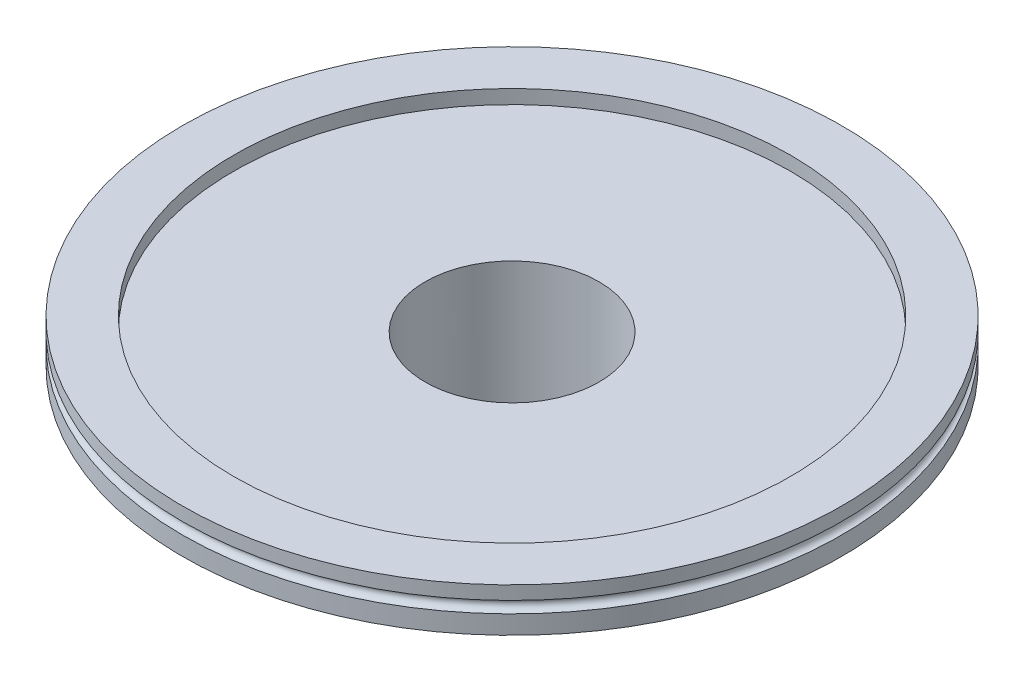
SolidWorks part; units mm, degrees
material "AISI 304"
ref_plane "Front Plane" through (0, 0, 0) normal (0, 0, 1) x (1, 0, 0)
ref_plane "Top Plane" through (0, 0, 0) normal (0, 1, 0) x (1, 0, 0)
ref_plane "Right Plane" through (0, 0, 0) normal (1, 0, 0) x (0, 0, -1)
sketch "Sketch1" plane through (0, 0, 0) normal (0, 0, 1) x (1, 0, 0)
  line L0 (-90, 5.969) -> (-90, -5.969)
  line L1 (-90, -5.969) -> (0, -5.969)
  line L6 (0, -5.969) -> (0, 0) construction
  line L7 (0, 0) -> (-90, 0) construction
  line L12 (-90, 5.969) -> (0, 5.969)
  line L13 (0, 5.969) -> (0, -5.969)
  dimension "D" = 11.938
  dimension "LF_Flange_Diam" = 180
revolve "Blank" add sketch "Sketch1" angle 360 about L13
sketch "Sketch7" plane through (0, 0, 0) normal (0, 0, 1) x (1, 0, 0)
  line L0 (-23.749, -5.969) -> (-23.749, 2.159)
  line L1 (90, 5.969) -> (-90, 5.969) construction
  line L2 (-23.749, 2.159) -> (-76.03, 2.159)
  line L3 (-76.03, 2.159) -> (-76.03, 5.969)
  line L4 (-76.03, 5.969) -> (0, 5.969)
  line L5 (0, 5.969) -> (0, -5.969)
  line L6 (0, -5.969) -> (-23.749, -5.969)
  line L7 (90, 5.969) -> (-90, 5.969) construction
  line L8 (0, 5.969) -> (0, 10.8934) construction
  line L9 (-90, -5.969) -> (90, -5.969) construction
  line L10 (-90, 5.969) -> (-90, -5.969) construction
  dimension "D1" = 13.97
  dimension "Tube ID Bottom" = 47.498
  dimension "Flange to Bore" = 3.81
revolve "Single Side Bore" cut sketch "Sketch7" angle 360 about L8
sketch "Sketch9" plane through (0, 0, 0) normal (0, 0, 1) x (1, 0, 0)
  line L0 (0, 5.969) -> (0, -35.4838) construction
  line L1 (30.3554, -34.925) -> (23.749, -34.925)
  line L2 (26.1239, -40.005) -> (37.465, -40.005)
  line L3 (37.465, -40.005) -> (37.465, -36.83)
  line L4 (37.465, -36.83) -> (30.3554, -34.925)
  line L5 (26.1239, -40.005) -> (26.1239, -37.3888)
  line L6 (23.749, -34.925) -> (23.749, -37.3888)
  line L7 (23.749, -37.3888) -> (26.1239, -37.3888)
  line L9 (0, -34.925) -> (0, -40.005) construction
  line L10 (90, 5.969) -> (-90, 5.969) construction
  dimension "Height" = 45.974
  dimension "D1" = 105
  dimension "D2" = 2.6162
  dimension "D3" = 3.175
  dimension "D4" = 74.93
  dimension "D5" = 52.2478
  dimension "D6" = 5.08
  dimension "D7" = 47.498
revolve "KF Flange" add sketch "Sketch9" angle 360 about L0
sketch "Sketch8" plane through (0, 0, 0) normal (0, 0, 1) x (1, 0, 0)
  line L0 (-23.749, 2.159) -> (-23.749, -13.081)
  line L1 (-23.749, -13.081) -> (-23.749, -22.1488)
  line L2 (-25.4, -22.1488) -> (-23.749, -22.1488) construction
  line L3 (-25.4, -13.081) -> (-23.749, -13.081) construction
  line L4 (76.03, 2.159) -> (-76.03, 2.159) construction
  line L5 (-26.1239, -37.3888) -> (26.1239, -37.3888) construction
  line L6 (-23.749, -37.3888) -> (-25.4, -37.3888)
  line L7 (-23.749, -37.3888) -> (-23.749, -22.1488)
  line L8 (-25.4, -37.3888) -> (-25.4, -22.1488)
  line L9 (-23.749, 2.159) -> (-23.749, -5.969) construction
  line L10 (-25.4, -22.1488) -> (-25.4, -13.081)
  line L11 (-25.4, -13.081) -> (-25.4, 2.159)
  line L13 (-25.4, 2.159) -> (-23.749, 2.159)
  line L14 (0, 0) -> (0, -25.3856) construction
  dimension "Top Tube ID" = 47.498
  dimension "Top Tube OD" = 50.8
  dimension "Bottom to Conical" = 19.05
revolve "Revolve1" add sketch "Sketch8" angle 360 about L14
sketch "Sketch13" plane through (0, 0, 0) normal (0, 0, 1) x (1, 0, 0)
  line L0 (-90, -5.969) -> (90, -5.969) construction
  line L1 (-87.46, -5.969) -> (-82.38, -5.969)
  line L2 (-87.46, -5.969) -> (-87.46, -3.937)
  line L3 (-87.46, -3.937) -> (-82.38, -3.937)
  line L4 (-82.38, -5.969) -> (-82.38, -3.937)
  line L5 (0, 0) -> (0, -3.0965) construction
  line L6 (-90, 5.969) -> (-90, -5.969) construction
  dimension "D1" = 2.032
  dimension "D2" = 5.08
  dimension "D3" = 2.54
revolve "Cut-Revolve2" cut sketch "Sketch13" angle 360 about L5
sketch "Sketch15" plane through (0, 0, 0) normal (0, 0, 1) x (1, 0, 0)
  line L0 (-90, 5.969) -> (-90, -5.969) construction
  line L1 (0, 0) -> (0, -5.0977) construction
  line L2 (-90, 2.286) -> (-90, -0.889)
  arc A0 (-90, 2.286) -> (-90, -0.889) centre (-90, 0.6985) cw
  dimension "D1" = 3.175
  dimension "D2" = 3.683
revolve "Cut-Revolve3" cut sketch "Sketch15" angle 360 about L1
ref_plane "Plane1" through (0, -41.91, 0) normal (0, -1, 0) x (-1, 0, 0)
ref_plane "Plane2" through (0, 7.969, 0) normal (0, 1, 0) x (1, 0, 0)
equation "\"Holes@Thru Hole Pattern\"=\"bolt holes\""
equation "\"D7@Sketch9\"=\"Top Tube ID@Sketch8\""
